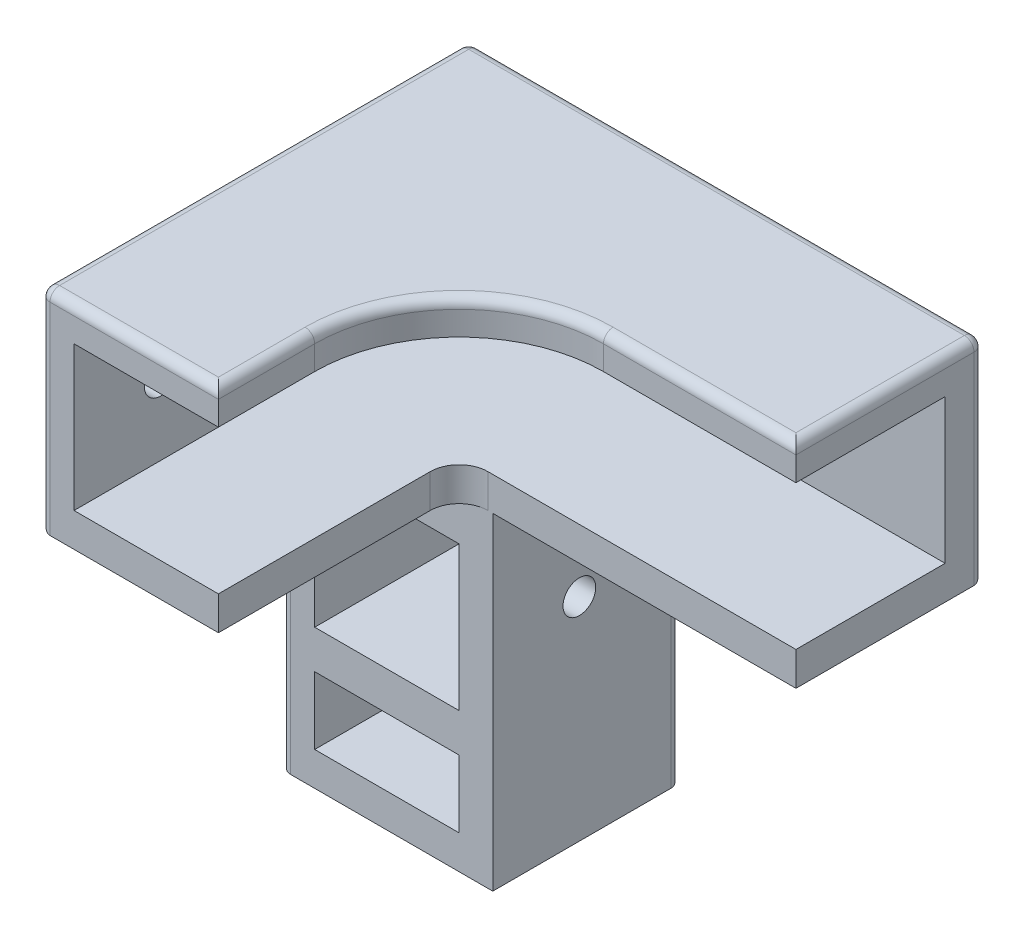
SolidWorks part; units mm, degrees
ref_plane "Front Plane" through (0, 0, 0) normal (0, 0, 1) x (1, 0, 0)
ref_plane "Top Plane" through (0, 0, 0) normal (0, 1, 0) x (1, 0, 0)
ref_plane "Right Plane" through (0, 0, 0) normal (1, 0, 0) x (0, 0, -1)
sketch "Sketch1" plane through (0, 0, 0) normal (0, 0, 1) x (1, 0, 0)
  line L1 (-5.6994, 32.9163) -> (16.3006, 32.9163)
  line L2 (-5.6994, 10.9163) -> (-5.6994, -23.0837)
  line L3 (-5.6994, -23.0837) -> (16.3006, -23.0837)
  line L4 (16.3006, 32.9163) -> (16.3006, -23.0837)
  line L5 (-5.6994, 10.9163) -> (-37.1994, 10.9163)
  line L7 (-5.6994, 32.9163) -> (-37.1994, 32.9163)
  line L8 (-37.1994, 10.9163) -> (-37.1994, 32.9163)
  dimension "D1" = 22
  dimension "D2" = 22
  dimension "D3" = 56
  dimension "D4" = 53.5
extrude "Boss-Extrude1" add sketch "Sketch1" along normal blind 19.5
sketch "Sketch3" plane through (0, 0, 19.5) normal (0, 0, 1) x (1, 0, 0)
  line L1 (16.3006, 32.9163) -> (-2.1994, 32.9163)
  line L2 (16.3006, 32.9163) -> (16.3006, 10.9163)
  line L3 (16.3006, 10.9163) -> (-2.1994, 10.9163)
  line L4 (-2.1994, 32.9163) -> (-2.1994, 10.9163)
  dimension "D1" = 18.5
extrude "Boss-Extrude2" add sketch "Sketch3" along normal blind 25
sketch "Sketch5" plane through (0, 0, 44.5) normal (0, 0, 1) x (1, 0, 0)
  line L0 (-37.1994, 32.9163) -> (-37.1994, 10.9163) construction
  line L1 (-37.1994, 29.4163) -> (12.8006, 29.4163)
  line L2 (-37.1994, 29.4163) -> (-37.1994, 14.4163)
  line L3 (-37.1994, 14.4163) -> (12.8006, 14.4163)
  line L4 (12.8006, 29.4163) -> (12.8006, 14.4163)
  line L5 (16.3006, 10.9163) -> (16.3006, 32.9163) construction
  line L6 (-2.1994, 6.4163) -> (12.8006, 6.4163)
  line L7 (-2.1994, 6.4163) -> (-2.1994, -8.5837)
  line L8 (-2.1994, -8.5837) -> (12.8006, -8.5837)
  line L9 (12.8006, 6.4163) -> (12.8006, -8.5837)
  line L12 (-2.1994, 32.9163) -> (-37.1994, 32.9163) construction
  line L13 (-2.1994, 10.9163) -> (16.3006, 10.9163) construction
  line L15 (16.3006, -23.0837) -> (16.3006, 10.9163) construction
  line L16 (-5.6994, -23.0837) -> (16.3006, -23.0837) construction
  line L17 (-2.1994, -12.5837) -> (12.8006, -12.5837)
  line L18 (-2.1994, -12.5837) -> (-2.1994, -19.5837)
  line L19 (-2.1994, -19.5837) -> (12.8006, -19.5837)
  line L20 (12.8006, -12.5837) -> (12.8006, -19.5837)
  dimension "D1" = 3.5
  dimension "D2" = 4.5
  dimension "D3" = 15
  dimension "D4" = 3.5
  dimension "D5" = 15
  dimension "D6" = 15
  dimension "D7" = 3.5
  dimension "D8" = 15
  dimension "D9" = 4
  dimension "D10" = 3.5
extrude "Cut-Extrude1" cut sketch "Sketch5" against normal offset from surface (40.5 mm away) 4 up to face at (-8.8661, 6.9163, 0)
sketch "Sketch7" plane through (16.3006, 0, 0) normal (1, 0, 0) x (0, 0, -1)
  line L0 (-34.5, 10.9163) -> (-19.5, 10.9163)
  line L1 (-44.5, 10.9163) -> (-19.5, 10.9163) construction
  line L2 (-19.5, 10.9163) -> (-19.5, -4.0837)
  line L3 (-19.5, -23.0837) -> (-19.5, 10.9163) construction
  arc A0 (-34.5, 10.9163) -> (-19.5, -4.0837) centre (-34.5, -4.0837) cw
  dimension "D1" = 15
extrude "Boss-Extrude4" add sketch "Sketch7" against normal blind 3.5
sketch "Sketch8" plane through (0, 0, 0) normal (0, 0, -1) x (-1, 0, 0)
  line L0 (5.6994, 10.9163) -> (20.6994, 10.9163)
  line L1 (37.1994, 10.9163) -> (5.6994, 10.9163) construction
  line L2 (5.6994, 10.9163) -> (5.6994, -4.0837)
  line L3 (5.6994, 10.9163) -> (5.6994, -23.0837) construction
  arc A0 (20.6994, 10.9163) -> (5.6994, -4.0837) centre (20.6994, -4.0837) ccw
  dimension "D1" = 15
extrude "Boss-Extrude5" add sketch "Sketch8" against normal blind 3.5
sketch "Sketch9" plane through (0, 32.9163, 0) normal (0, 1, 0) x (1, 0, 0)
  line L0 (-2.1994, -34.5) -> (-2.1994, -19.5)
  line L1 (-2.1994, -44.5) -> (-2.1994, -19.5) construction
  line L2 (-2.1994, -19.5) -> (-17.1994, -19.5)
  line L3 (-2.1994, -19.5) -> (-37.1994, -19.5) construction
  arc A0 (-2.1994, -34.5) -> (-17.1994, -19.5) centre (-17.1994, -34.5) ccw
  dimension "D1" = 15
extrude "Boss-Extrude6" add sketch "Sketch9" against normal blind 3.5
fillet "Fillet3" radius 3 1 edges
sketch "Sketch11" plane through (0, 0, 0) normal (0, 0, -1) x (-1, 0, 0)
  line L0 (1.1994, -23.0837) -> (1.1994, 10.9163) construction
  line L2 (5.6994, -23.0837) -> (-16.3006, -23.0837) construction
  line L5 (5.6994, -4.0837) -> (5.6994, -23.0837) construction
  text T0 "MR.3" font "Century Gothic" height 12
  dimension "D1" = 4.5
extrude "Cut-Extrude3" cut sketch "Sketch11" against normal blind 1
sketch "Sketch12" plane through (0, 0, 0) normal (0, 0, -1) x (-1, 0, 0)
  line L0 (37.1994, 21.9163) -> (-16.3006, 21.9163) construction
  line L1 (37.1994, 32.9163) -> (37.1994, 10.9163) construction
  line L2 (-16.3006, -23.0837) -> (-16.3006, 32.9163) construction
  line L3 (-12.8006, 14.4163) -> (-12.8006, 29.4163) construction
  circle A0 centre (-5.3006, 21.9163) radius 1.7
  circle A1 centre (10.9494, 21.9163) radius 1.7
  circle A2 centre (27.1994, 21.9163) radius 1.7
  dimension "D4" = 3.4
  dimension "D1" = 7.5
  dimension "D2" = 10
  dimension "D3" = 16.25
extrude "Cut-Extrude4" cut sketch "Sketch12" against normal blind 5
sketch "Sketch13" plane through (-5.6994, 0, 0) normal (-1, 0, 0) x (0, 0, 1)
  line L0 (4, 6.4163) -> (19.5, 6.4163) construction
  line L1 (19.5, 10.9163) -> (19.5, -23.0837) construction
  circle A0 centre (10.5, -1.0837) radius 1.7
  dimension "D2" = 9
  dimension "D3" = 3.4
  dimension "D1" = 7.5
extrude "Cut-Extrude5" cut sketch "Sketch13" against normal blind 45
sketch "Sketch14" plane through (16.3006, 0, 0) normal (1, 0, 0) x (0, 0, -1)
  line L0 (-10.5, -1.0837) -> (-10.5, 32.9163) construction
  line L1 (-44.5, 32.9163) -> (0, 32.9163) construction
  line L2 (-44.5, 21.9163) -> (-10.5, 21.9163) construction
  line L3 (-44.5, 10.9163) -> (-44.5, 32.9163) construction
  circle A0 centre (-10.5, 21.9163) radius 1.7
  circle A1 centre (-35.5, 21.9163) radius 1.7
  dimension "D1" = 3.4
  dimension "D2" = 9
extrude "Cut-Extrude6" cut sketch "Sketch14" against normal blind 45
sketch "Sketch15" plane through (0, -23.0837, 0) normal (0, -1, 0) x (1, 0, 0)
  line L0 (16.3006, 9.75) -> (-5.6994, 9.75) construction
  line L1 (16.3006, 19.5) -> (16.3006, 0) construction
  line L2 (-5.6994, 19.5) -> (-5.6994, 0) construction
  line L3 (5.3006, 19.5) -> (5.3006, 0) construction
  line L4 (-5.6994, 19.5) -> (16.3006, 19.5) construction
  line L5 (-5.6994, 0) -> (16.3006, 0) construction
  circle A0 centre (5.3006, 9.75) radius 1.7
  dimension "D1" = 3.4
extrude "Cut-Extrude7" cut sketch "Sketch15" against normal blind 4
mirror "Mirror2" about plane through (16.3006, 32.9163, 19.5) normal (-1, 0, 0) of "Cut-Extrude7", "Cut-Extrude6", "Cut-Extrude5", "Cut-Extrude4", "Fillet3", "Boss-Extrude6", "Boss-Extrude5", "Boss-Extrude4", "Cut-Extrude1", "Boss-Extrude2", "Boss-Extrude1"
sketch "Sketch16" plane through (0, 0, 0) normal (0, 0, -1) x (-1, 0, 0)
  line L0 (-69.8006, 32.9163) -> (37.1994, 32.9163) construction
  line L1 (-16.3006, 32.9163) -> (53.9943, 32.9163)
  line L2 (-16.3006, 32.9163) -> (-16.3006, -24.95)
  line L3 (-16.3006, -24.95) -> (53.9943, -24.95)
  line L4 (53.9943, 32.9163) -> (53.9943, -24.95)
extrude "Cut-Extrude8" cut sketch "Sketch16" against normal blind 72
sketch "Sketch20" plane through (0, 0, 0) normal (0, 0, -1) x (-1, 0, 0)
  line L0 (-20.8006, -23.0837) -> (-20.8006, 10.9163) construction
  line L1 (-16.3006, -23.0837) -> (-38.3006, -23.0837) construction
  line L2 (-16.3006, 32.9163) -> (-16.3006, -23.0837) construction
  text T0 "MR.3" font "Century Gothic" height 12
  dimension "D1" = 4.5
extrude "Cut-Extrude9" cut sketch "Sketch20" against normal blind 1
fillet "Fillet4" radius 1 17 edges at (25.5506, 32.9163, 44.5) (69.8006, 32.9163, 9.75) (69.8006, 21.9163, 0) (61.5506, 10.9163, 0) (34.8006, 32.9163, 39.5) (38.3006, -13.5837, 0) (42.694, 6.5229, 0) (39.194, 32.9163, 23.8934) (16.3006, 32.9163, 22.25) (16.3006, 4.9163, 0) (16.3006, 21.9163, 44.5) (16.3006, 10.9163, 39.5) (16.3006, -13.5837, 19.5) (16.3006, 6.5229, 23.8934) (43.0506, 32.9163, 0)
